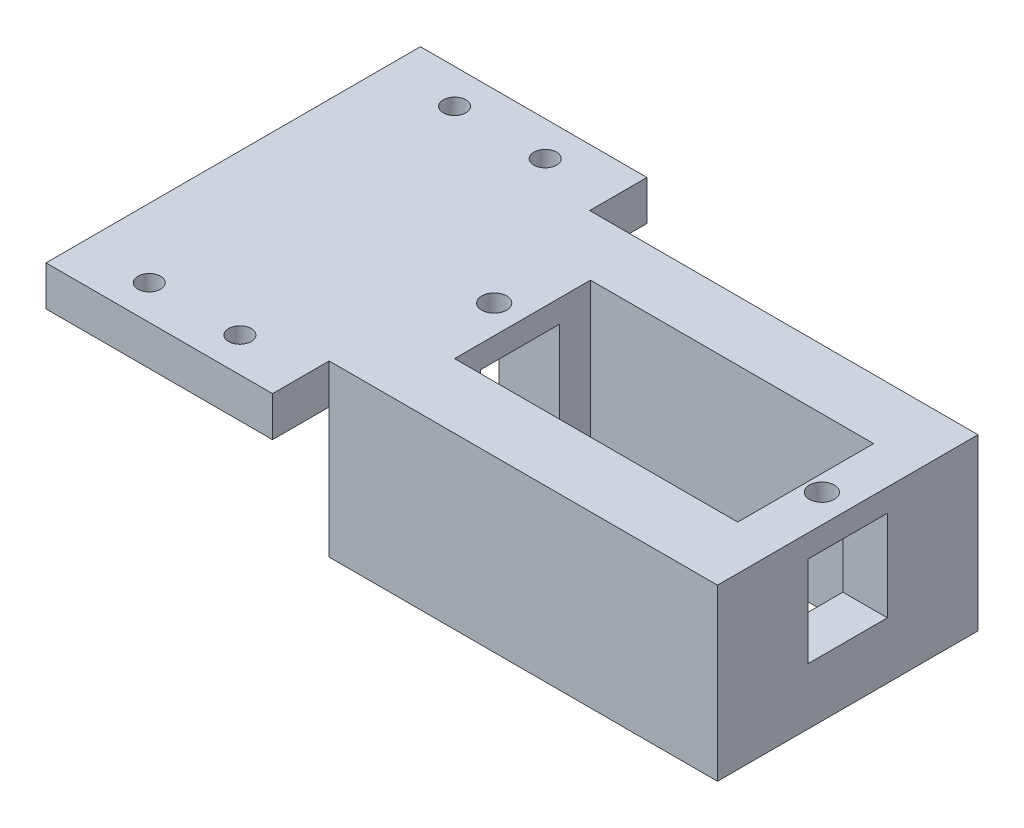
SolidWorks part; units mm, degrees
ref_plane "Plan de face" through (0, 0, 0) normal (0, 0, 1) x (1, 0, 0)
ref_plane "Plan de dessus" through (0, 0, 0) normal (0, 1, 0) x (1, 0, 0)
ref_plane "Plan de droite" through (0, 0, 0) normal (1, 0, 0) x (0, 0, -1)
sketch "Esquisse1" plane through (0, 0, 0) normal (0, 1, 0) x (1, 0, 0)
  line L0 (-6.3571, 7.25) -> (18.6429, 7.25)
  line L1 (-6.3571, 7.25) -> (-6.3571, -4.75)
  line L2 (18.6429, 7.25) -> (18.6429, -4.75)
  line L3 (-6.3571, -4.75) -> (18.6429, -4.75)
  line L4 (-11.7143, 12.5357) -> (22.5714, 12.5357)
  line L5 (-11.7143, 12.5357) -> (-11.7143, -10.4643)
  line L6 (22.5714, 12.5357) -> (22.5714, -10.4643)
  line L7 (-11.7143, -10.4643) -> (22.5714, -10.4643)
  dimension "D1" = 25
  dimension "D2" = 12
extrude "Boss.-Extru.1" add sketch "Esquisse1" along normal blind 15
sketch "Esquisse2" plane through (-11.7143, 0, 0) normal (-1, 0, 0) x (0, 0, 1)
  line L0 (-1.0357, 15) -> (-1.0357, 13)
  line L1 (-12.5357, 15) -> (10.4643, 15) construction
  line L2 (2.4643, 13) -> (-4.5357, 13)
  line L3 (2.4643, 13) -> (2.4643, 5)
  line L4 (2.4643, 5) -> (-4.5357, 5)
  line L5 (-4.5357, 5) -> (-4.5357, 13)
  point P6 (-1.0357, 13)
extrude "Enlèv. mat.-Extru.1" cut sketch "Esquisse2" against normal blind 60 contours L5 L4 L3 L2
sketch "Esquisse3" plane through (0, 15, 0) normal (0, 1, 0) x (1, 0, 0)
  line L0 (18.6429, 1.25) -> (22.5714, 1.25)
  line L1 (18.6429, -4.75) -> (18.6429, 7.25) construction
  line L2 (22.5714, -10.4643) -> (22.5714, 12.5357) construction
  line L3 (22.5714, 1.25) -> (17.5714, 1.25)
  line L4 (-6.3571, 1.25) -> (-11.3571, 1.25)
  line L7 (-6.3571, 7.25) -> (-6.3571, -4.75) construction
  circle A0 centre (-8.8571, 1.25) radius 1.1
  circle A1 centre (20.0714, 1.25) radius 1.1
extrude "Enlèv. mat.-Extru.2" cut sketch "Esquisse3" against normal blind 10 contours A0 | A1
sketch "Esquisse4" plane through (-11.7143, 0, 0) normal (-1, 0, 0) x (0, 0, 1)
  line L0 (-4.5357, 13) -> (-4.5357, 15)
  line L2 (-4.5357, 15) -> (-12.5162, 15)
  line L4 (-12.5357, 15) -> (10.4643, 15) construction
  line L6 (2.4643, 13) -> (2.4643, 15)
  line L8 (2.4643, 15) -> (10.387, 15)
  line L11 (2.4643, 13) -> (2.4643, 11.4779)
  line L13 (2.4643, 11.4779) -> (10.387, 11.4779)
  line L14 (-4.5357, 13) -> (-4.5357, 11.4779)
  line L16 (-4.5357, 11.4779) -> (-12.5952, 11.4779)
  line L19 (-4.5357, 5) -> (-4.5357, 13) construction
  line L20 (10.4643, 15) -> (15.4643, 15)
  line L21 (10.387, 11.4779) -> (15.4643, 11.4779)
  line L22 (15.4643, 15) -> (15.4643, 11.4779)
  line L23 (-12.5952, 11.4779) -> (-17.5952, 11.4779)
  line L24 (-17.5952, 11.4779) -> (-17.5952, 15)
  line L25 (-17.5952, 15) -> (-12.5162, 15)
  line L26 (10.4643, 15) -> (10.387, 15)
extrude "Boss.-Extru.2" add sketch "Esquisse4" along normal blind 20
sketch "Esquisse6" plane through (0, 15, 0) normal (0, 1, 0) x (1, 0, 0)
  line L0 (-11.7143, -10.4643) -> (-11.7143, 12.5357)
  line L1 (-11.7143, 13.5357) -> (-11.7143, -11.4643)
  line L2 (-11.7143, -15.4643) -> (-11.7143, -10.4643) construction
  line L3 (-11.6457, 14.5419) -> (-16.6457, 14.5419)
  line L4 (-16.6457, 14.5419) -> (-18.6457, 14.5419)
  line L5 (-18.6457, 14.5419) -> (-24.6457, 14.5419)
  line L6 (-24.6457, 14.5419) -> (-26.6457, 14.5419)
  line L7 (-11.6361, -12.4238) -> (-16.6361, -12.4238)
  line L8 (-16.6361, -12.4238) -> (-18.6361, -12.4238)
  line L9 (-18.6361, -12.4238) -> (-24.6361, -12.4238)
  line L10 (-24.6361, -12.4238) -> (-26.6361, -12.4238)
  line L11 (22.5714, 12.5357) -> (-31.7143, 12.5357) construction
  line L12 (-11.7143, -11.4643) -> (-11.7143, -12.4643)
  line L13 (-11.7143, 13.5357) -> (-11.7143, 14.5357)
  line L14 (-11.7143, 12.5357) -> (-11.7143, 17.5952) construction
  circle A4 centre (-25.6457, 14.5419) radius 1
  circle A5 centre (-17.6457, 14.5419) radius 1
  circle A6 centre (-25.6361, -12.4238) radius 1
  circle A7 centre (-17.6361, -12.4238) radius 1
  point P9 (-11.7143, 1.0357)
  dimension "D7" = 90
  dimension "D1" = 5
  dimension "D2" = 2
  dimension "D3" = 6
  dimension "D4" = 5
  dimension "D5" = 2
  dimension "D6" = 6
  dimension "D8" = 23
  dimension "D9" = 25
sketch "Esquisse7" plane through (-31.7143, 0, 0) normal (-1, 0, 0) x (0, 0, 1)
  line L0 (10.4643, 11.4779) -> (-12.5357, 11.4779)
  line L1 (-12.5357, 11.4779) -> (-12.5357, 0)
  line L2 (-12.5357, 0) -> (10.4643, 0)
  line L3 (10.4643, 0) -> (10.4643, 11.4779)
extrude "Enlèv. mat.-Extru.3" cut sketch "Esquisse7" against normal blind 20
extrude "Enlèv. mat.-Extru.4" cut sketch "Esquisse6" against normal blind 20
